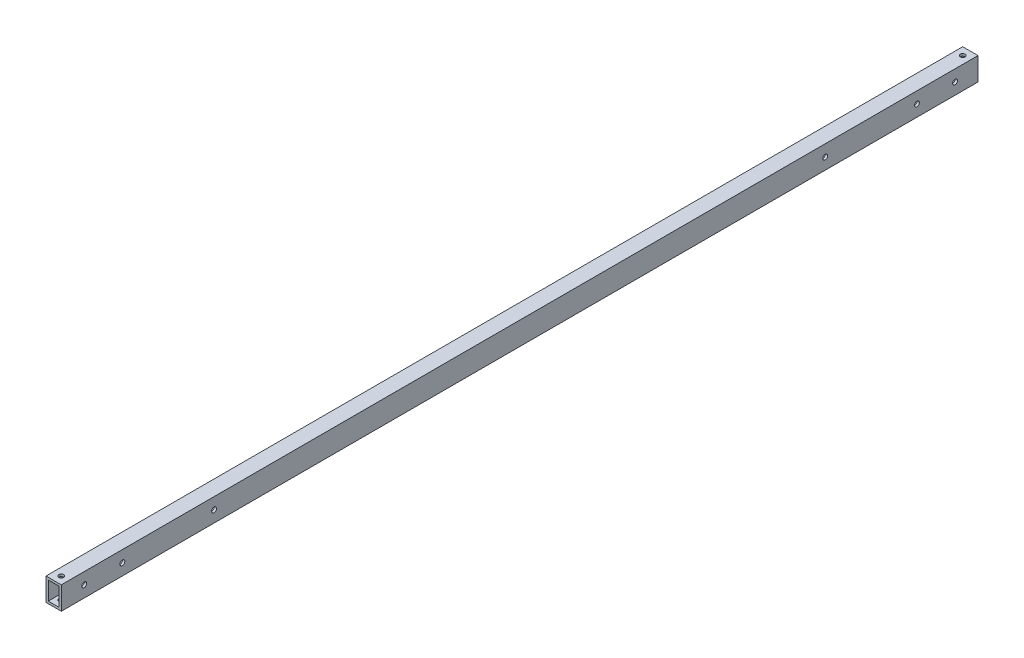
SolidWorks part; units mm, degrees
material "6063-T5"
ref_plane "正面" through (0, 0, 0) normal (0, 0, 1) x (1, 0, 0)
ref_plane "平面" through (0, 0, 0) normal (0, 1, 0) x (1, 0, 0)
ref_plane "右側面" through (0, 0, 0) normal (1, 0, 0) x (0, 0, -1)
sketch "ｽｹｯﾁ1" plane through (0, 0, 0) normal (0, 0, 1) x (1, 0, 0)
  line L1 (-5, -7.5) -> (5, -7.5)
  line L2 (-5, -7.5) -> (-5, 7.5)
  line L3 (-5, 7.5) -> (5, 7.5)
  line L4 (5, -7.5) -> (5, 7.5)
  line L5 (-5, -7.5) -> (5, 7.5) construction
  line L6 (-5, 7.5) -> (5, -7.5) construction
  point P0 (0, 0)
  dimension "D1" = 10
  dimension "D2" = 15
extrude "押し出し-薄板1" add sketch "ｽｹｯﾁ1" along normal blind 600 thin thin type one direction reverse wall 1.5
sketch "ｽｹｯﾁ2" plane through (0, 7.5, 0) normal (0, 1, 0) x (1, 0, 0)
  line L0 (0, 0) -> (0, -600) construction
  line L1 (5, -600) -> (-5, -600) construction
  line L2 (-5, -300) -> (5, -300) construction
  line L3 (-5, -600) -> (-5, 0) construction
  line L4 (5, -600) -> (5, 0) construction
  circle A0 centre (0, -595) radius 1.6
  circle A1 centre (0, -5) radius 1.6
  dimension "D1" = 5
  dimension "D2" = 3.2
extrude "ｶｯﾄ - 押し出し1" cut sketch "ｽｹｯﾁ2" against normal through all
sketch "ｽｹｯﾁ3" plane through (5, 0, 0) normal (1, 0, 0) x (0, 0, -1)
  line L0 (-600, 0) -> (0, 0) construction
  line L1 (-600, -7.5) -> (-600, 7.5) construction
  line L2 (0, -7.5) -> (0, 7.5) construction
  line L3 (-300, 7.5) -> (-300, -7.5) construction
  line L4 (-600, 7.5) -> (0, 7.5) construction
  line L5 (-600, -7.5) -> (0, -7.5) construction
  circle A0 centre (-560, 0) radius 1.6
  circle A1 centre (-40, 0) radius 1.6
  circle A2 centre (-500, 0) radius 1.6
  circle A3 centre (-100, 0) radius 1.6
  circle A4 centre (-585, 0) radius 1.6
  circle A5 centre (-15, 0) radius 1.6
  dimension "D1" = 40
  dimension "D2" = 3.2
  dimension "D3" = 60
  dimension "D4" = 15
extrude "ｶｯﾄ - 押し出し2" cut sketch "ｽｹｯﾁ3" against normal through all
